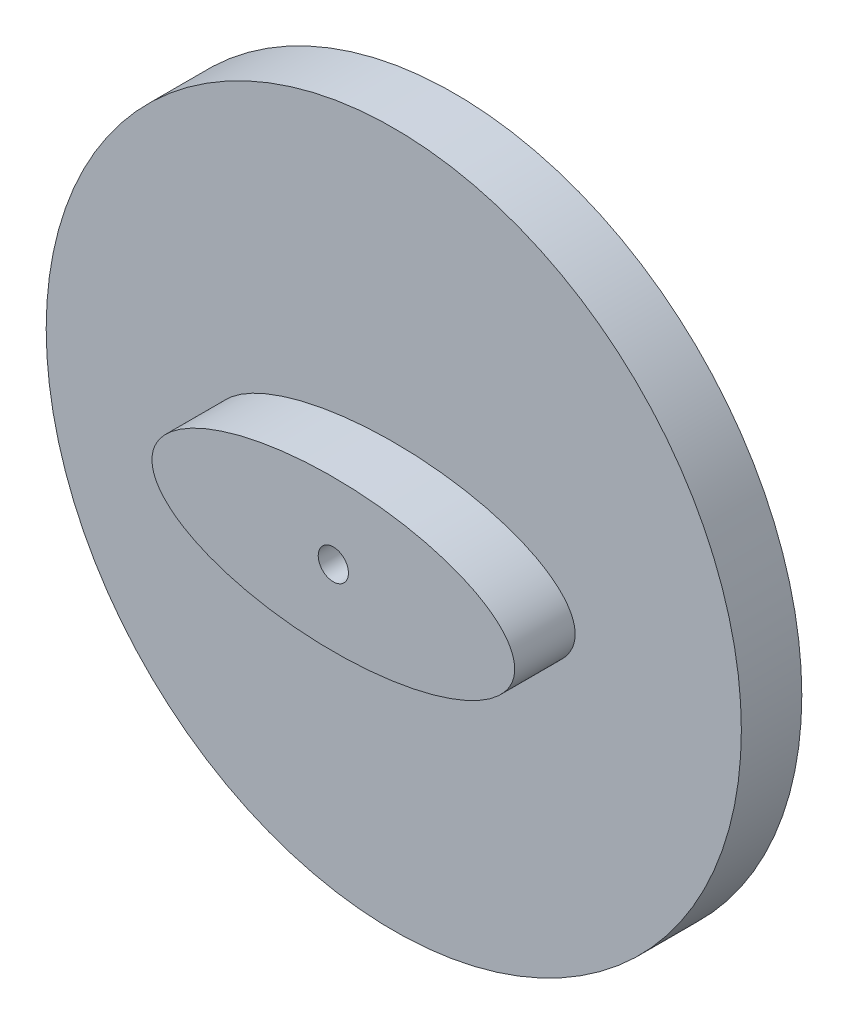
SolidWorks part; units mm, degrees
ref_plane "Plan de face" through (0, 0, 0) normal (0, 0, 1) x (1, 0, 0)
ref_plane "Plan de dessus" through (0, 0, 0) normal (0, 1, 0) x (1, 0, 0)
ref_plane "Plan de droite" through (0, 0, 0) normal (1, 0, 0) x (0, 0, -1)
sketch "Esquisse1" plane through (0, 0, 0) normal (0, 0, 1) x (1, 0, 0)
  circle A1 centre (0, 0) radius 11.5
  dimension "D2" = 23
extrude "Boss.-Extru.1" add sketch "Esquisse1" along normal blind 2 contours A1
sketch "Esquisse6" plane through (0, 0, 2) normal (0, 0, 1) x (1, 0, 0)
  ellipse E0 centre (0, 0) end of major axis (6, 0) minor radius 2.5
extrude "Boss.-Extru.5" add sketch "Esquisse6" along normal blind 2
sketch "Esquisse7" plane through (0, 0, 0) normal (0, 0, -1) x (-1, 0, 0)
  circle A0 centre (0, 0) radius 0.5
extrude "Enlèv. mat.-Extru.1" cut sketch "Esquisse7" against normal through all
